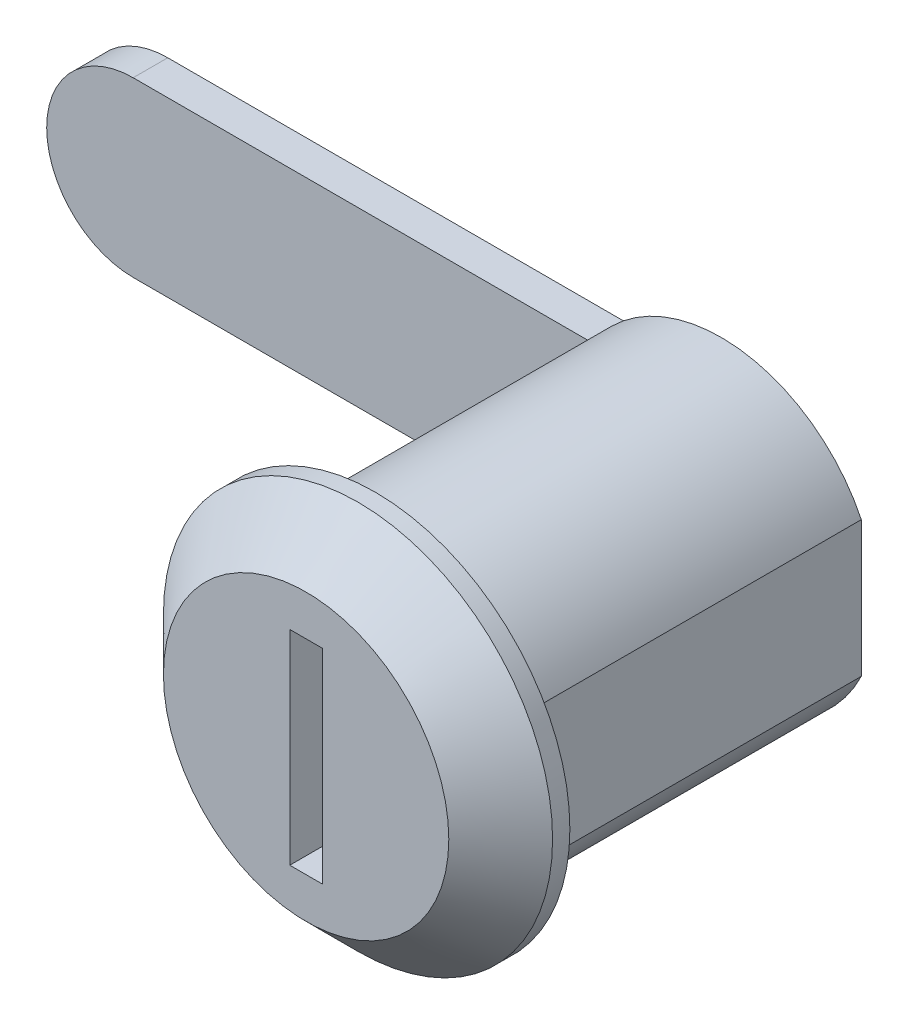
SolidWorks part; units mm, degrees
ref_plane "前视基准面" through (0, 0, 0) normal (0, 0, 1) x (1, 0, 0)
ref_plane "上视基准面" through (0, 0, 0) normal (0, 1, 0) x (1, 0, 0)
ref_plane "右视基准面" through (0, 0, 0) normal (1, 0, 0) x (0, 0, -1)
sketch "草图1" plane through (0, 0, 0) normal (0, 0, 1) x (1, 0, 0)
  circle A0 centre (0, 0) radius 11.25
  dimension "D1" = 22.5
extrude "凸台-拉伸1" add sketch "草图1" along normal blind 4
sketch "草图2" plane through (0, 0, 4) normal (0, 0, 1) x (1, 0, 0)
  line L1 (-0.945, -5.9032) -> (0.945, -5.9032)
  line L2 (-0.945, -5.9032) -> (-0.945, 5.9032)
  line L3 (-0.945, 5.9032) -> (0.945, 5.9032)
  line L4 (0.945, -5.9032) -> (0.945, 5.9032)
  line L5 (-0.945, -5.9032) -> (0.945, 5.9032) construction
  line L6 (-0.945, 5.9032) -> (0.945, -5.9032) construction
  point P0 (0, 0)
  point P6 (0.945, 5.9032)
extrude "切除-拉伸1" cut sketch "草图2" against normal blind 2
sketch "草图3" plane through (0, 0, 0) normal (0, 0, -1) x (-1, 0, 0)
  line L0 (0, 11.25) -> (0, -11.25) construction
  line L1 (-8.1, -3.923) -> (-8.1, 3.923)
  line L2 (8.1, -3.923) -> (8.1, 3.923)
  arc A0 (-8.1, -3.923) -> (8.1, -3.923) centre (0, 0) ccw
  circle A1 centre (0, 0) radius 11.25 construction
  arc A2 (8.1, 3.923) -> (-8.1, 3.923) centre (0, 0) ccw
  dimension "D1" = 18
  dimension "D2" = 16.2
  dimension "D3" = 7.846
extrude "凸台-拉伸2" add sketch "草图3" along normal blind 20
sketch "草图4" plane through (0, 0, -20) normal (0, 0, -1) x (-1, 0, 0)
  line L0 (0, 0) -> (34, 0) construction
  line L1 (0, 5) -> (34, 5)
  line L2 (0, -5) -> (34, -5)
  arc A0 (0, 5) -> (0, -5) centre (0, 0) ccw
  arc A1 (34, -5) -> (34, 5) centre (34, 0) ccw
  point P3 (17, 0)
  point P8 (39, 0)
  dimension "D1" = 10
  dimension "D2" = 39
extrude "凸台-拉伸3" add sketch "草图4" along normal blind 2
chamfer "倒角1" distance 3 angle 45 1 edges at (11.25, 0, 4)
